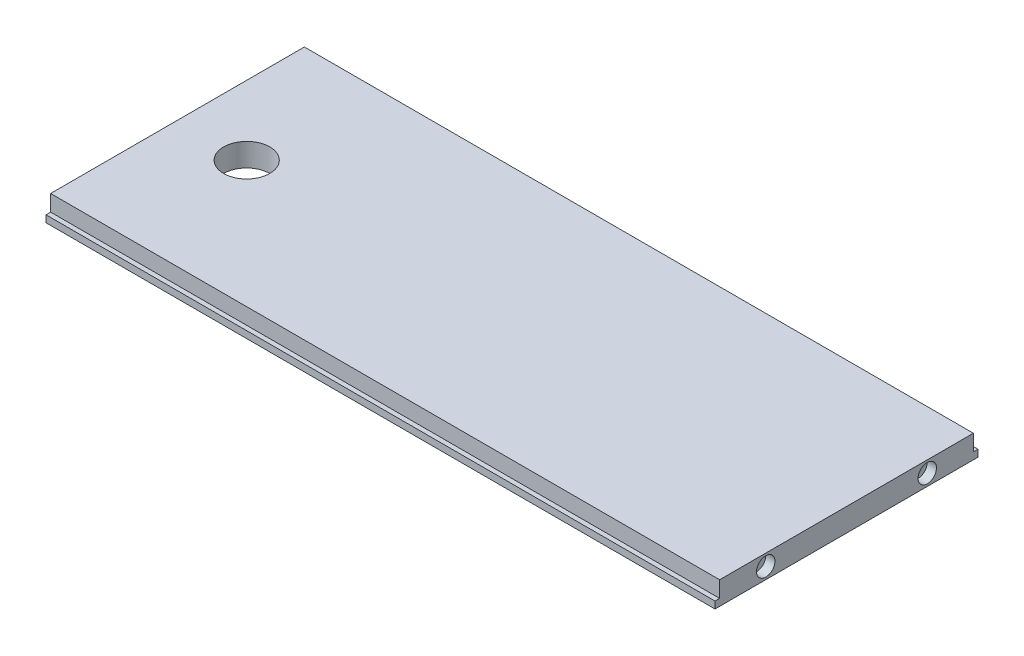
SolidWorks part; units mm, degrees
ref_plane "Front Plane" through (0, 0, 0) normal (0, 0, 1) x (1, 0, 0)
ref_plane "Top Plane" through (0, 0, 0) normal (0, 1, 0) x (1, 0, 0)
ref_plane "Right Plane" through (0, 0, 0) normal (1, 0, 0) x (0, 0, -1)
sketch "Sketch1" plane through (0, 0, 0) normal (0, 1, 0) x (1, 0, 0)
  line L1 (0, 0) -> (290, 0)
  line L2 (0, 0) -> (0, 114)
  line L3 (0, 114) -> (290, 114)
  line L4 (290, 0) -> (290, 114)
  dimension "D1" = 114
  dimension "D2" = 290
extrude "Boss-Extrude1" add sketch "Sketch1" along normal blind 10
sketch "Sketch2" plane through (0, 10, 0) normal (0, 1, 0) x (1, 0, 0)
  line L0 (290, 0) -> (290, 114) construction
  line L1 (0, 114) -> (290, 114)
  line L2 (0, 114) -> (0, 112)
  line L3 (0, 112) -> (290, 112)
  line L4 (290, 114) -> (290, 112)
  line L6 (0, 0) -> (290, 0)
  line L7 (0, 0) -> (0, 2)
  line L8 (0, 2) -> (290, 2)
  line L9 (290, 0) -> (290, 2)
  dimension "D1" = 2
  dimension "D2" = 2
extrude "Cut-Extrude1" cut sketch "Sketch2" against normal blind 7
sketch "Sketch3" plane through (290, 0, 0) normal (1, 0, 0) x (0, 0, -1)
  line L0 (112, 3) -> (112, 10) construction
  line L1 (2, 3) -> (2, 10) construction
  line L2 (0, 0) -> (114, 0) construction
  circle A0 centre (22, 5) radius 4
  circle A1 centre (92, 5) radius 4
  dimension "D1" = 8
  dimension "D2" = 8
  dimension "D3" = 20
  dimension "D5" = 5
  dimension "D6" = 5
  dimension "D4" = 20
extrude "Cut-Extrude2" cut sketch "Sketch3" against normal blind 4
sketch "Sketch4" plane through (0, 10, 0) normal (0, 1, 0) x (1, 0, 0)
  line L0 (0, 112) -> (0, 2) construction
  line L1 (290, 2) -> (0, 2) construction
  circle A0 centre (30, 57) radius 10
  dimension "D1" = 20
  dimension "D2" = 30
  dimension "D3" = 55
extrude "Cut-Extrude3" cut sketch "Sketch4" against normal blind 10
